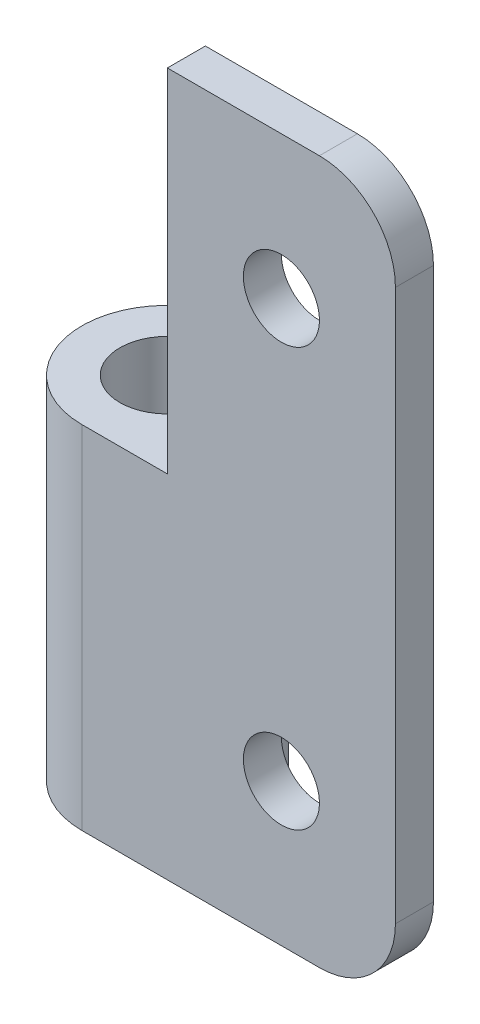
SolidWorks part; units mm, degrees
ref_plane "前视基准面" through (0, 0, 0) normal (0, 0, 1) x (1, 0, 0)
ref_plane "上视基准面" through (0, 0, 0) normal (0, 1, 0) x (1, 0, 0)
ref_plane "右视基准面" through (0, 0, 0) normal (1, 0, 0) x (0, 0, -1)
sketch "草图1" plane through (0, 0, 0) normal (0, 1, 0) x (1, 0, 0)
  line L0 (0, -4.5) -> (16.5, -4.5)
  line L1 (16.5, -4.5) -> (16.5, -2.5)
  line L2 (16.5, -2.5) -> (3.7417, -2.5)
  arc A0 (3.7417, -2.5) -> (0, -4.5) centre (0, 0) ccw
  circle A1 centre (0, 0) radius 2.5
  dimension "D1" = 9
  dimension "D2" = 5
  dimension "D3" = 16.5
  dimension "D4" = 2
extrude "凸台-拉伸1" add sketch "草图1" along normal blind 18.5
sketch "草图2" plane through (0, 18.5, 0) normal (0, 1, 0) x (1, 0, 0)
  line L0 (0, -4.5) -> (16.5, -4.5) construction
  line L1 (16.5, -2.5) -> (4.5, -2.5)
  line L2 (16.5, -2.5) -> (16.5, -4.5)
  line L3 (16.5, -4.5) -> (4.5, -4.5)
  line L4 (4.5, -2.5) -> (4.5, -4.5)
  dimension "D1" = 12
extrude "凸台-拉伸2" add sketch "草图2" along normal blind 18.5
sketch "草图3" plane through (0, 0, 2.5) normal (0, 0, -1) x (-1, 0, 0)
  line L0 (-16.5, 18.5) -> (-4.5, 18.5) construction
  line L1 (-16.5, 37) -> (-16.5, 0) construction
  circle A0 centre (-10.5, 7.5) radius 2
  circle A1 centre (-10.5, 29.5) radius 2
  dimension "D1" = 4
  dimension "D2" = 22
  dimension "D3" = 10.5
extrude "切除-拉伸1" cut sketch "草图3" against normal up to next
fillet "圆角1" radius 4 2 edges at (16.5, 37, 3.5) (16.5, 0, 3.5)
